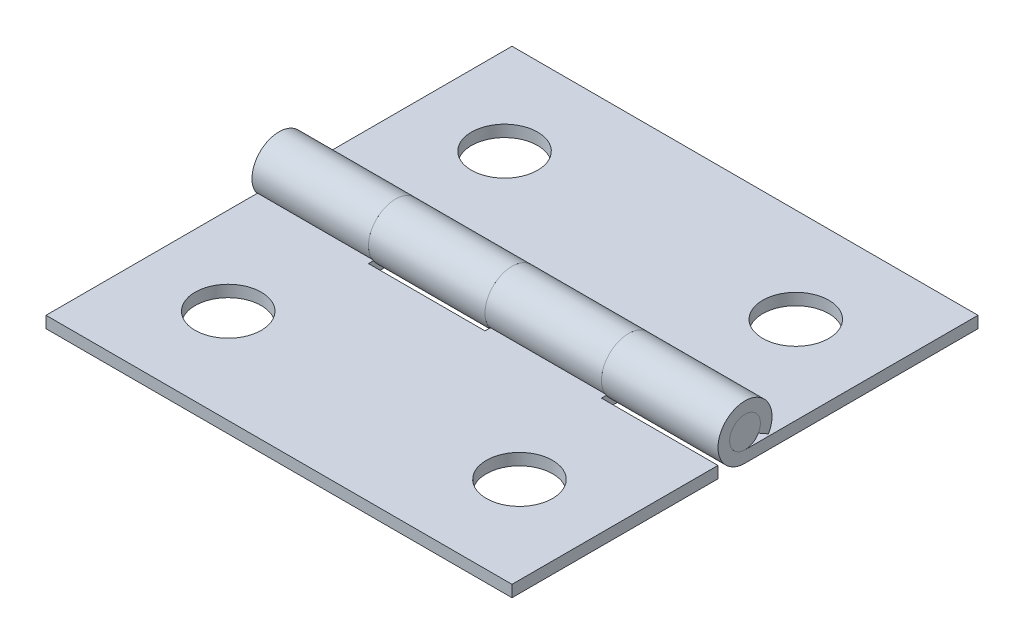
SolidWorks part; units mm, degrees
ref_plane "Front Plane" through (0, 0, 0) normal (0, 0, 1) x (1, 0, 0)
ref_plane "Top Plane" through (0, 0, 0) normal (0, 1, 0) x (1, 0, 0)
ref_plane "Right Plane" through (0, 0, 0) normal (1, 0, 0) x (0, 0, -1)
sketch "Sketch1" plane through (0, 0, 0) normal (0, 1, 0) x (1, 0, 0)
  line L0 (-12.7, 0) -> (12.7, 0) construction
  line L1 (-12.7, -12.7) -> (-12.7, 12.7) construction
  line L2 (-12.7, -12.7) -> (-7.9248, -12.7) construction
  line L4 (-7.9248, -12.7) -> (7.9502, -12.7) construction
  line L5 (12.7254, -12.7) -> (12.7254, -7.5438) construction
  line L6 (7.9502, -12.7) -> (12.7254, -12.7) construction
  line L7 (-12.7, 12.7) -> (-7.9248, 12.7) construction
  line L8 (-7.9248, 12.7) -> (7.9502, 12.7) construction
  line L9 (7.9502, 12.7) -> (23.8252, 12.7) construction
  line L10 (23.8252, 12.7) -> (28.6004, 12.7) construction
  line L11 (7.9502, -9.3472) -> (7.9502, -5.7404) construction
  line L12 (7.9502, -7.5438) -> (12.7254, -7.5438) construction
  point P3 (7.9502, -9.3472)
  point P4 (0, 0)
  point P8 (-12.7, 0)
  point P17 (-6.35, 0)
  point P21 (7.9502, -7.5438)
  dimension "Frame Leaf Height" = 25.4
  dimension "Overall Width" = 25.4
  dimension "Hole to End 1" = 4.7752
  dimension "Hole to End 2" = 4.7752
  dimension "D1" = 4.7752
  dimension "D2" = 4.7752
  dimension "D4" = 15.875
  dimension "D6" = 15.875
  dimension "Knuckle Length" = 6.35
  dimension "Hole Chamfer Dia" = 3.6068
  dimension "Hole Center to Pin" = 7.5438
  dimension "Door Leaf Height" = 25.4254
  dimension "Mounting Hole Diameter" = 3.6068
  dimension "D3" = 15.875
  dimension "Frame Leaf Width" = 12.7
  dimension "Door Leaf Width" = 12.7
sketch "Sketch2" plane through (0, 0, 0) normal (1, 0, 0) x (0, 0, -1)
  line L2 (0, -1.4732) -> (0, -0.8382) construction
  line L4 (0, 0.8382) -> (0, -0.8382) construction
  point P8 (0, 0)
  dimension "Leaf Thickness" = 0.635
  dimension "Pin Diameter" = 1.6764
sketch "Sketch3" plane through (0, 0, 0) normal (1, 0, 0) x (0, 0, -1)
  line L3 (0, 0) -> (-1.4732, -0.8382) construction
  line L4 (0, -1.4732) -> (-12.7, -1.4732)
  line L5 (-12.7, -1.4732) -> (-12.7, -0.8382)
  line L7 (-12.7, -0.8382) -> (0, -0.8382)
  line L8 (-12.7, 0) -> (12.7, 0) construction
  line L9 (-0.7285, -0.4145) -> (-1.2805, -0.7285)
  line L11 (-1.4732, 0) -> (-1.4732, -0.8382) construction
  circle A4 centre (0, 0) radius 0.8382 construction
  circle A5 centre (0, 0) radius 1.4732 construction
  arc A8 (-0.7285, -0.4145) -> (0, -0.8382) centre (0, 0) cw
  arc A9 (-1.2805, -0.7285) -> (0, -1.4732) centre (0, 0) cw
  point P0 (-1.2805, -0.7285)
  point P13 (-0.7285, -0.4145)
extrude "Boss-Extrude1" add sketch "Sketch3" along normal mid plane 25.4
sketch "Sketch4" plane through (0, 0, 0) normal (0, 1, 0) x (1, 0, 0)
  line L0 (-12.7, -1.4732) -> (12.7, -1.4732) construction
  line L1 (-12.7, -1.4732) -> (12.7, -1.4732) construction
  line L2 (12.7, 1.4732) -> (-12.7, 1.4732) construction
  line L3 (12.7, 1.4732) -> (-12.7, 1.4732) construction
  line L4 (-6.35, -1.4732) -> (-6.35, 1.4732)
  line L6 (-6.35, 1.4732) -> (0, 1.4732)
  line L7 (0, -1.4732) -> (-6.35, -1.4732)
  line L8 (0, 1.4732) -> (0, -1.4732)
  point P8 (-6.35, 0)
  dimension "D1" = 6.35
extrude "Cut-Extrude1" cut sketch "Sketch4" against normal through all both and the other way through all
pattern_linear "LPattern1" count 6 spacing 12.7 along (1, 0, 0) of "Cut-Extrude1"
sketch "Sketch5" plane through (0, -0.8382, 0) normal (0, 1, 0) x (1, 0, 0)
  line L0 (7.9502, -7.5438) -> (-7.9248, -7.5438) construction
  line L1 (0, -7.5438) -> (0, -12.7) construction
  line L2 (-7.9248, -7.5438) -> (-7.9248, -12.7) construction
  line L3 (12.7, -12.7) -> (-12.7, -12.7) construction
  circle A0 centre (7.9502, -7.5438) radius 1.8034
  circle A2 centre (-7.9248, -7.5438) radius 1.8034
extrude "Cut-Extrude2" cut sketch "Sketch5" against normal through all
sketch "Sketch9" plane through (0, 0, 0) normal (0, 1, 0) x (1, 0, 0)
  circle A0 centre (7.9502, -7.5438) radius 1.8034
  circle A2 centre (-7.9248, -7.5438) radius 1.8034
  dimension "D1" = 3.6068
pattern_circular "CirPattern1" count 2 over 360 about axis through (0, 0, 0) along (0, 1, 0) of bodies 107
sketch "Sketch6" plane through (0, 0, 0) normal (1, 0, 0) x (0, 0, -1)
  circle A0 centre (0, 0) radius 0.8382
  dimension "D1" = 1.6764
extrude "Boss-Extrude2" add sketch "Sketch6" along normal mid plane 25.4 separate body
sketch "Sketch7" plane through (0, 0, 0) normal (1, 0, 0) x (0, 0, -1)
  line L0 (-0.8382, 0) -> (0.8382, 0) construction
  line L1 (-12.7, 0) -> (12.7, 0) construction
  line L2 (12.7, -0.8382) -> (12.7, -1.4732) construction
  line L3 (12.7, -0.8382) -> (12.7, -1.4732) construction
  line L4 (12.7, -1.4732) -> (-12.7, -1.4732) construction
  line L5 (-12.7, -1.4732) -> (-12.7, -0.8382)
  point P6 (0, 0)
  point P8 (0.8382, 0)
  point P9 (-0.8382, 0)
  point P12 (12.7, -0.8382)
  point P13 (12.7, -1.4732)
  point P14 (-12.7, -1.4732)
  dimension "D1" = 1.6764
  dimension "D2" = 25.4
  dimension "D3" = 0.635
sketch "Sketch8" plane through (0, 0, 0) normal (0, 1, 0) x (1, 0, 0)
  line L0 (-9.7282, -7.5438) -> (-6.1214, -7.5438) construction
  line L2 (6.1468, -7.5438) -> (9.7536, -7.5438) construction
  line L3 (-7.9248, -5.7404) -> (-7.9248, -9.3472) construction
  line L5 (7.9502, -5.7404) -> (7.9502, -9.3472) construction
  line L6 (-7.9502, 9.3472) -> (-7.9502, 5.7404) construction
  line L7 (-9.7536, 7.5438) -> (-6.1468, 7.5438) construction
  line L10 (7.9248, 9.3472) -> (7.9248, 5.7404) construction
  line L11 (6.1214, 7.5438) -> (9.7282, 7.5438) construction
  circle A1 centre (-7.9248, -7.5438) radius 1.8034 construction
  circle A3 centre (7.9502, -7.5438) radius 1.8034 construction
  circle A4 centre (-7.9502, 7.5438) radius 1.8034 construction
  circle A6 centre (7.9248, 7.5438) radius 1.8034 construction
  circle A7 centre (7.9248, 7.5438) radius 1.8034 construction
  point P2 (-12.7, 0)
  point P7 (-7.9248, -7.5438)
  point P19 (7.9502, -7.5438)
  point P25 (-12.7, 12.7)
  point P26 (28.6004, 12.7)
  point P28 (-12.7, -12.7)
  point P30 (12.7254, -12.7)
  point P32 (-9.7282, -7.5438)
  point P33 (-7.9248, -5.7404)
  point P34 (-6.1214, -7.5438)
  point P35 (-7.9248, -9.3472)
  point P40 (9.7536, -7.5438)
  point P41 (7.9502, -9.3472)
  point P42 (6.1468, -7.5438)
  point P43 (7.9502, -5.7404)
  point P67 (7.9502, -12.7)
  point P69 (-7.9248, -12.7)
  point P71 (-7.9248, 12.7)
  point P73 (-7.9502, 7.5438)
  point P76 (7.9248, 7.5438)
  point P77 (23.8252, 12.7)
  point P78 (7.9502, 12.7)
  point P82 (-7.9502, 9.3472)
  point P83 (-9.7536, 7.5438)
  point P84 (-7.9502, 5.7404)
  point P85 (-6.1468, 7.5438)
  point P90 (7.9248, 5.7404)
  point P91 (6.1214, 7.5438)
  point P92 (7.9248, 9.3472)
  point P93 (9.7282, 7.5438)
equation "\"D1@Sketch1\"=\"Hole to End 1@Sketch1\""
equation "\"D2@Sketch1\"=\"Hole to End 2@Sketch1\""
equation "\"D6@Sketch1\"=\"D4@Sketch1\""
equation "\"hinge_height\"= 1"
equation "\"D1@Boss-Extrude1\"=\"hinge_height\""
equation "\"D1@Sketch4\"=\"Knuckle Length@Sketch1\""
equation "\"D3@LPattern1\"=\"Knuckle Length@Sketch1\"*2"
equation "\"D1@Sketch6\"=\"Pin Diameter@Sketch2\""
equation "\"D1@Boss-Extrude2\" = \"Frame Leaf Height@Sketch1\""
equation "\"D1@Sketch7\"=\"Pin Diameter@Sketch2\""
equation "\"D2@Sketch7\"=\"Overall Width@Sketch1\""
equation "\"D3@Sketch7\"=\"Leaf Thickness@Sketch2\""
equation "\"Knuckle Length@Sketch1\"=\"Frame Leaf Height@Sketch1\" / 4"
equation "\"Hole to End 2@Sketch1\"=\"Hole to End 1@Sketch1\""
equation "\"hinge_diameter\"= 0.142"
equation "\"D1@Sketch9\"=\"hinge_diameter\""
equation "\"Mounting Hole Diameter@Sketch1\"=\"hinge_diameter\""
equation "\"Hole Chamfer Dia@Sketch1\"=\"hinge_diameter\""
